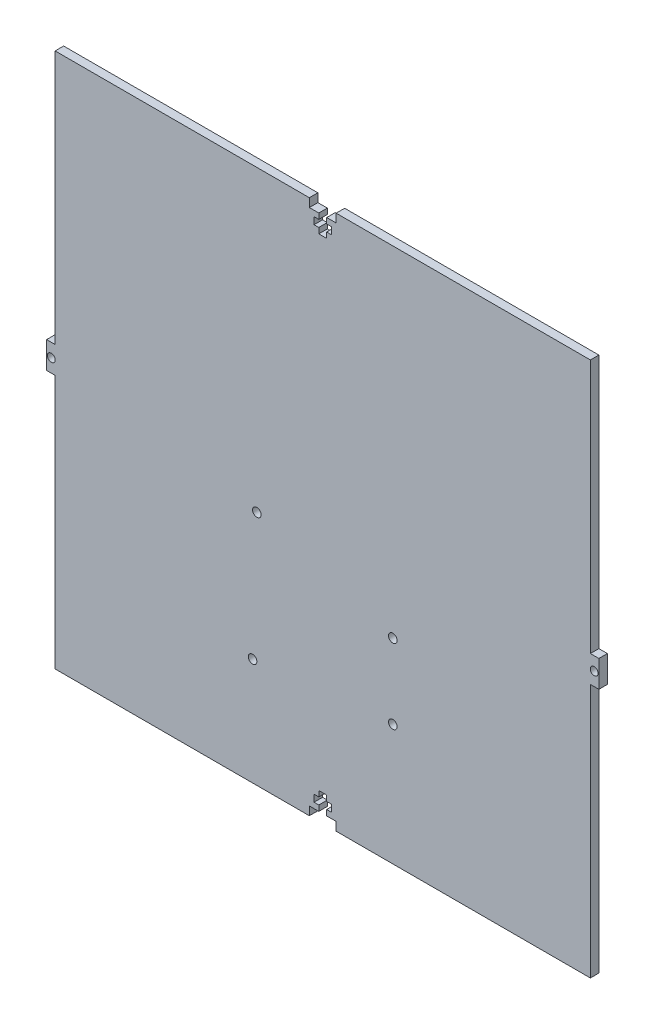
SolidWorks part; units mm, degrees
ref_plane "Front Plane" through (0, 0, 0) normal (0, 0, 1) x (1, 0, 0)
ref_plane "Top Plane" through (0, 0, 0) normal (0, 1, 0) x (1, 0, 0)
ref_plane "Right Plane" through (0, 0, 0) normal (1, 0, 0) x (0, 0, -1)
sketch "Sketch2" plane through (0, 0, 0) normal (0, 0, 1) x (1, 0, 0)
  line L1 (-100, -100) -> (100, -100)
  line L2 (-100, -100) -> (-100, 100)
  line L3 (-100, 100) -> (100, 100)
  line L4 (100, -100) -> (100, 100)
  line L5 (-100, -100) -> (100, 100) construction
  line L6 (-100, 100) -> (100, -100) construction
  point P0 (0, 0)
  dimension "D1" = 200
  dimension "D2" = 200
extrude "Boss-Extrude1" add sketch "Sketch2" along normal blind 3.18
sketch "Sketch3" plane through (0, 0, 3.18) normal (0, 0, 1) x (1, 0, 0)
  line L0 (100, 100) -> (-100, 100) construction
  line L1 (-5, 100) -> (5, 100)
  line L2 (-5, 100) -> (-5, 96.82)
  line L3 (-5, 96.82) -> (-1.47, 96.82)
  line L4 (5, 100) -> (5, 96.82)
  line L5 (0, 100) -> (0, 25.4128) construction
  line L6 (1.47, 92.14) -> (3.25, 92.14)
  line L8 (-1.47, 96.82) -> (-1.47, 94.74)
  line L9 (-1.47, 90.07) -> (1.47, 90.07)
  line L10 (1.47, 96.82) -> (1.47, 94.74)
  line L11 (-3.25, 94.74) -> (-1.47, 94.74)
  line L12 (-3.25, 94.74) -> (-3.25, 92.14)
  line L13 (-3.25, 92.14) -> (-1.47, 92.14)
  line L14 (3.25, 94.74) -> (3.25, 92.14)
  line L15 (-1.47, 92.14) -> (-1.47, 90.07)
  line L16 (1.47, 94.74) -> (3.25, 94.74)
  line L17 (1.47, 96.82) -> (5, 96.82)
  line L18 (1.47, 92.14) -> (1.47, 90.07)
  line L19 (-100, 0) -> (100, 0) construction
  line L20 (-100, 100) -> (-100, -100) construction
  line L21 (100, -100) -> (100, 100) construction
  line L22 (1.47, -96.82) -> (5, -96.82)
  line L23 (5, -100) -> (5, -96.82)
  line L24 (-5, -100) -> (5, -100)
  line L25 (-5, -100) -> (-5, -96.82)
  line L26 (-5, -96.82) -> (-1.47, -96.82)
  line L27 (-1.47, -96.82) -> (-1.47, -94.74)
  line L28 (-3.25, -94.74) -> (-1.47, -94.74)
  line L29 (-3.25, -94.74) -> (-3.25, -92.14)
  line L30 (-3.25, -92.14) -> (-1.47, -92.14)
  line L31 (-1.47, -92.14) -> (-1.47, -90.07)
  line L32 (-1.47, -90.07) -> (1.47, -90.07)
  line L33 (1.47, -92.14) -> (1.47, -90.07)
  line L34 (1.47, -92.14) -> (3.25, -92.14)
  line L35 (3.25, -94.74) -> (3.25, -92.14)
  line L36 (1.47, -94.74) -> (3.25, -94.74)
  line L37 (1.47, -96.82) -> (1.47, -94.74)
  dimension "D1" = 3.18
  dimension "D2" = 10
  dimension "D3" = 2.94
  dimension "D4" = 2.6
  dimension "D5" = 6.75
  dimension "D6" = 6.5
  dimension "D7" = 2.08
extrude "Cut-Extrude1" cut sketch "Sketch3" against normal through all
sketch "Sketch4" plane through (-100, 0, 0) normal (-1, 0, 0) x (0, 0, 1)
  line L0 (0, 100) -> (0, -100) construction
  line L1 (0, -5) -> (3.18, -5)
  line L2 (0, -5) -> (0, 5)
  line L3 (0, 5) -> (3.18, 5)
  line L4 (3.18, -5) -> (3.18, 5)
  line L5 (3.18, 100) -> (3.18, -100) construction
  line L6 (0, 0) -> (19.9881, 0) construction
  dimension "D1" = 10
extrude "Boss-Extrude2" add sketch "Sketch4" along normal blind 3.18
sketch "Sketch6" plane through (0, 0, 3.18) normal (0, 0, 1) x (1, 0, 0)
  line L0 (-103.18, 0) -> (0, 0) construction
  line L1 (-103.18, -5) -> (-103.18, 5) construction
  circle A1 centre (-101.43, 0) radius 1.47
  dimension "D1" = 2.94
  dimension "D2" = 1.75
extrude "Cut-Extrude2" cut sketch "Sketch6" against normal through all
mirror "Mirror1" about plane through (0, 0, 0) normal (1, 0, 0) of "Boss-Extrude2"
mirror "Mirror2" about plane through (0, 0, 0) normal (1, 0, 0) of "Cut-Extrude2"
sketch "Sketch7" plane through (0, 0, 3.18) normal (0, 0, 1) x (1, 0, 0)
  circle A0 centre (26.1794, -54.818) radius 1.6
  circle A1 centre (26.1794, -26.918) radius 1.6
  circle A2 centre (-24.6206, -11.618) radius 1.6
  circle A3 centre (-26.2206, -59.918) radius 1.6
extrude "Cut-Extrude3" cut sketch "Sketch7" against normal through all
